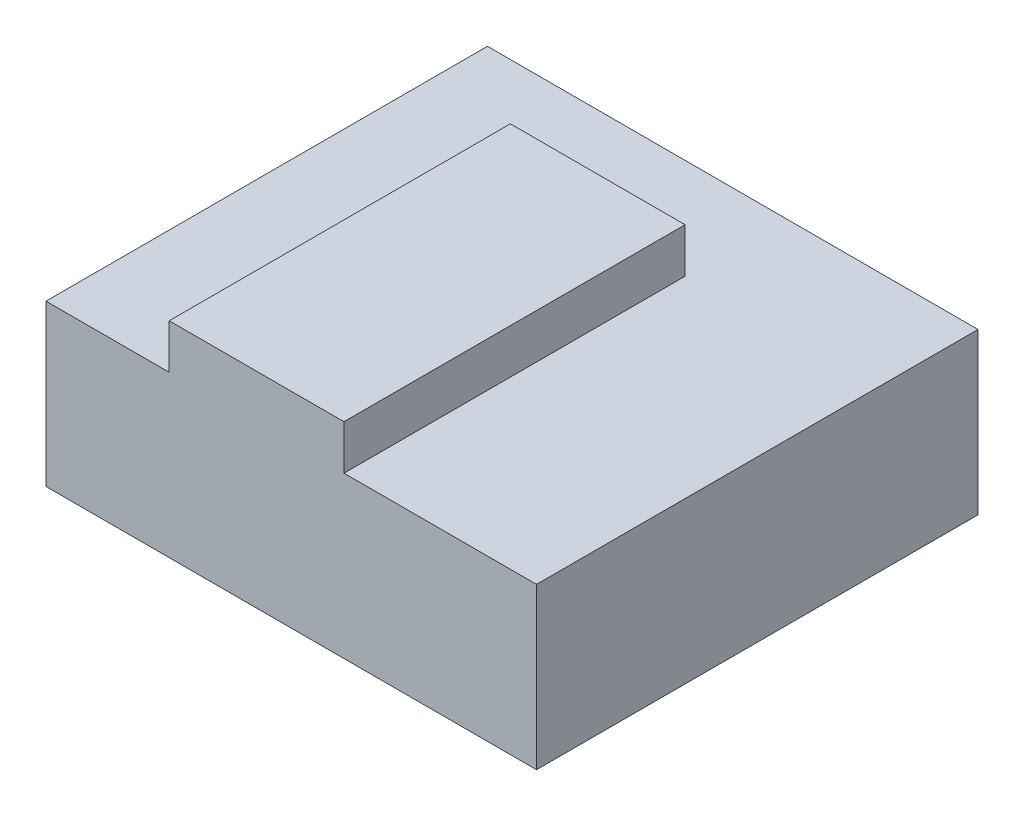
SolidWorks part; units mm, degrees
ref_plane "Front Plane" through (0, 0, 0) normal (0, 0, 1) x (1, 0, 0)
ref_plane "Top Plane" through (0, 0, 0) normal (0, 1, 0) x (1, 0, 0)
ref_plane "Right Plane" through (0, 0, 0) normal (1, 0, 0) x (0, 0, -1)
sketch "Sketch1" plane through (0, 0, 0) normal (0, 1, 0) x (1, 0, 0)
  line L1 (0, 0) -> (110, 0)
  line L2 (0, 0) -> (0, 99)
  line L3 (0, 99) -> (110, 99)
  line L4 (110, 0) -> (110, 99)
  dimension "D1" = 110
  dimension "D2" = 99
extrude "Boss-Extrude1" add sketch "Sketch1" along normal blind 46
sketch "Sketch2" plane through (0, 46, 0) normal (0, 1, 0) x (1, 0, 0)
  line L0 (0, 0) -> (110, 0) construction
  line L1 (66.819, 0) -> (27.6267, 0)
  line L2 (66.819, 0) -> (66.819, 76.5035)
  line L3 (66.819, 76.5035) -> (27.6267, 76.5035)
  line L4 (27.6267, 0) -> (27.6267, 76.5035)
  line L6 (0, 0) -> (110, 0)
  line L7 (0, 0) -> (0, 99)
  line L8 (0, 99) -> (110, 99)
  line L9 (110, 0) -> (110, 99)
  line M1 (0, 99) -> (0, 0)
  line M2 (0, 0) -> (110, 0)
  line M3 (110, 0) -> (110, 99)
  line M4 (110, 99) -> (0, 99)
extrude "Cut-Extrude1" cut sketch "Sketch2" against normal blind 10 contours L4 L3 L2 M2 M3 M4 M1
